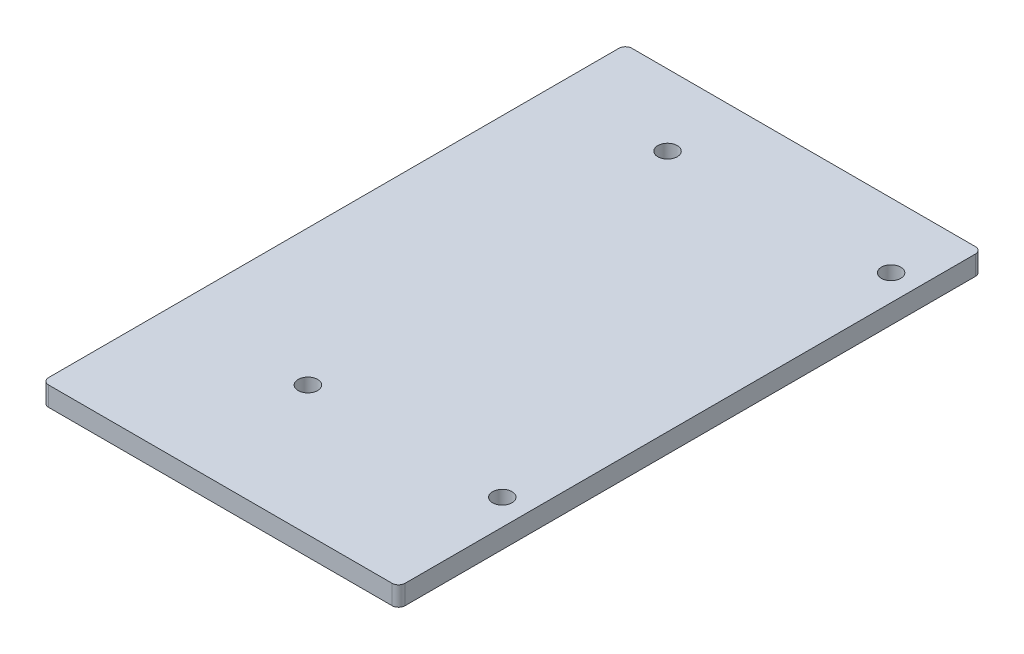
SolidWorks part; units mm, degrees
material "A-玻璃纤维"
ref_plane "前视基准面" through (0, 0, 0) normal (0, 0, 1) x (1, 0, 0)
ref_plane "上视基准面" through (0, 0, 0) normal (0, 1, 0) x (1, 0, 0)
ref_plane "右视基准面" through (0, 0, 0) normal (1, 0, 0) x (0, 0, -1)
other "Configuration Table"
sketch "草图1" plane through (0, 0, 0) normal (0, 1, 0) x (1, 0, 0)
  line L0 (0, 0) -> (32.1044, 0) construction
  line L5 (0, 0) -> (0, -29.04) construction
  line L7 (0, 0) -> (55, 0)
  line L8 (0, 0) -> (0, -90)
  line L9 (0, -90) -> (55, -90)
  line L10 (55, 0) -> (55, -90)
  circle A0 centre (17.5, -11) radius 1.5
  circle A1 centre (51, -10) radius 1.5
  circle A2 centre (21, -70) radius 1.5
  circle A3 centre (51, -70) radius 1.5
  dimension "D3" = 3
  dimension "D4" = 3
  dimension "D5" = 3
  dimension "D6" = 3
  dimension "D1" = 55
  dimension "D2" = 90
  dimension "D7" = 17.5
  dimension "D8" = 11
  dimension "D9" = 10
  dimension "D10" = 51
  dimension "D11" = 21
  dimension "D12" = 70
  dimension "D13" = 70
  dimension "D14" = 51
extrude "凸台-拉伸1" add sketch "草图1" along normal blind 3
fillet "圆角1" radius 1 4 edges at (55, 1.5, 0) (0, 1.5, 0) (0, 1.5, 90) (55, 1.5, 90)
